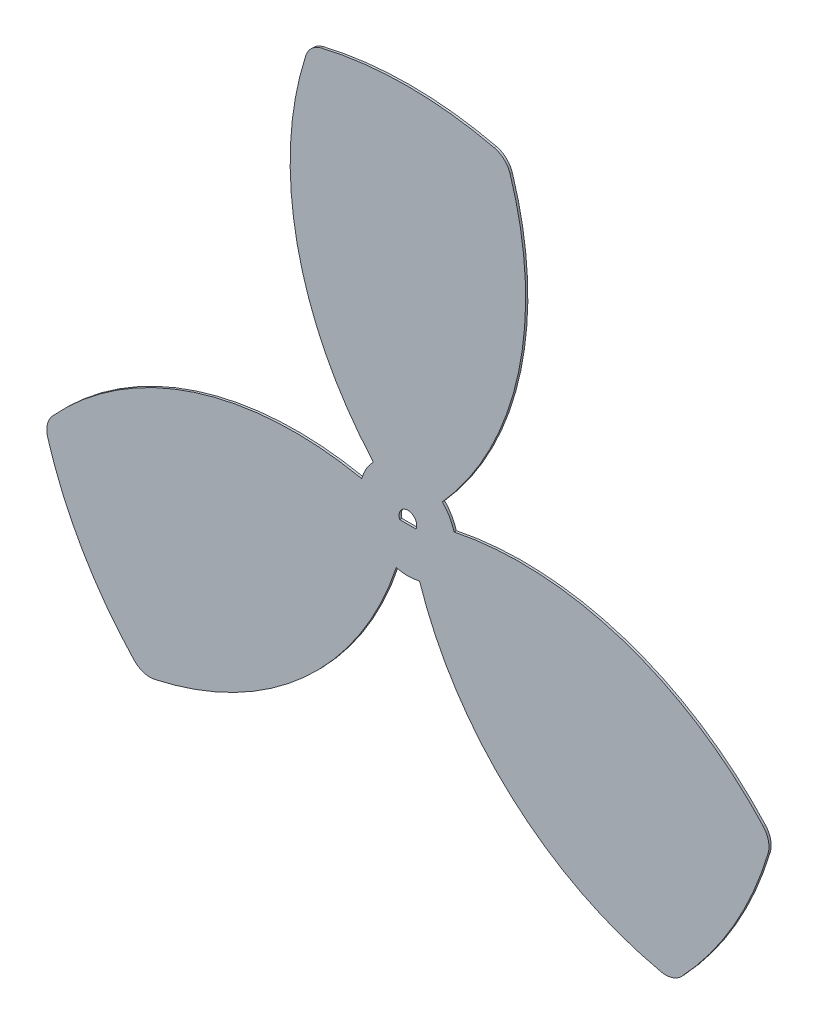
SolidWorks part; units mm, degrees
ref_plane "Plan de face" through (0, 0, 0) normal (0, 0, 1) x (1, 0, 0)
ref_plane "Plan de dessus" through (0, 0, 0) normal (0, 1, 0) x (1, 0, 0)
ref_plane "Plan de droite" through (0, 0, 0) normal (1, 0, 0) x (0, 0, -1)
sketch "Esquisse2" plane through (0, 0, 0) normal (0, 0, 1) x (1, 0, 0)
  line L0 (-43.229, 36.5855) -> (-43.229, 206.5855)
  circle A0 centre (-43.229, 36.5855) radius 21.7168
  arc A1 (1.1818, 200.682) -> (-87.6398, 200.682) centre (-43.229, 36.5855) ccw
  arc A2 (-87.6398, 200.682) -> (-43.229, 36.5855) centre (51.7427, 150.3464) ccw
  arc A3 (1.1818, 200.682) -> (-43.229, 36.5855) centre (-138.2007, 150.3464) cw
  arc A4 (121.0882, -7.0019) -> (-43.229, 36.5855) centre (7.805, -102.5428) ccw
  arc A5 (76.6774, -83.9237) -> (121.0882, -7.0019) centre (-43.229, 36.5855) ccw
  arc A6 (76.6774, -83.9237) -> (-43.229, 36.5855) centre (102.7767, 61.9529) cw
  arc A7 (-163.1354, -83.9237) -> (-43.229, 36.5855) centre (-189.2347, 61.9529) ccw
  arc A8 (-207.5462, -7.0019) -> (-163.1354, -83.9237) centre (-43.229, 36.5855) ccw
  arc A9 (-207.5462, -7.0019) -> (-43.229, 36.5855) centre (-94.263, -102.5428) cw
  point P18 (-43.229, 36.5855)
  dimension "D1" = 3
  dimension "D2" = 170
extrude "Boss.-Extru.1" add sketch "Esquisse2" along normal blind 1 contours A9 A8 A7 A0 | A6 A5 A4 A0 | A3 A1 L0 A0 | A1 A2 A0 L0 | A9 A0 A7 | A6 A0 A4 | A7 A0 A6 | A0 A9 A2 | A0 A2 L0 | A3 A0 L0 | A4 A0 A3
sketch "Esquisse4" plane through (0, 0, 0) normal (0, 0, -1) x (-1, 0, 0)
  line L0 (43.229, 14.8687) -> (43.229, 206.5855) construction
  line L1 (-103.9953, -48.4145) -> (62.0363, 47.4439) construction
  line L2 (46.9371, 35.0855) -> (39.5209, 35.0855)
  arc A0 (37.9538, 15.5192) -> (48.5042, 15.5192) centre (43.229, 36.5855) ccw construction
  arc A2 (39.5209, 35.0855) -> (46.9371, 35.0855) centre (43.229, 36.5855) cw
  arc A5 (87.6398, 200.682) -> (-1.1818, 200.682) centre (43.229, 36.5855) ccw construction
  arc A6 (-121.0882, -7.0019) -> (-76.6774, -83.9237) centre (43.229, 36.5855) ccw construction
  arc A7 (64.1106, 42.5502) -> (58.8354, 51.6871) centre (43.229, 36.5855) ccw construction
  point P16 (43.229, 36.5855)
  point P17 (43.229, 40.5855)
  dimension "D1" = 5.5
  dimension "D2" = 7.4162
  dimension "D3" = 4
extrude "Enlèv. mat.-Extru.2" cut sketch "Esquisse4" against normal through all
fillet "Congé2" radius 10 6 edges at (121.0882, -7.0019, 0.5) (76.6774, -83.9237, 0.5) (-163.1354, -83.9237, 0.5) (-207.5462, -7.0019, 0.5) (-87.6398, 200.682, 0.5) (1.1818, 200.682, 0.5)
